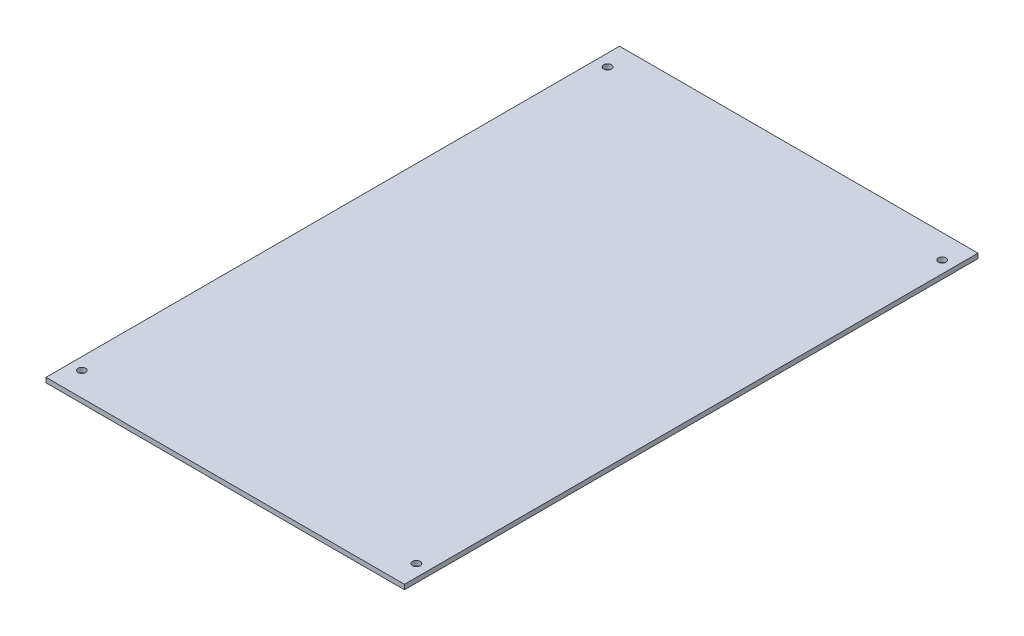
SolidWorks part; units mm, degrees
ref_plane "Front" through (0, 0, 0) normal (0, 0, 1) x (1, 0, 0)
ref_plane "Top" through (0, 0, 0) normal (0, 1, 0) x (1, 0, 0)
ref_plane "Right" through (0, 0, 0) normal (1, 0, 0) x (0, 0, -1)
sketch "Эскиз1" plane through (0, 0, 0) normal (0, 1, 0) x (1, 0, 0)
  line L1 (0, 0) -> (150, 0)
  line L2 (0, 0) -> (0, 240)
  line L3 (0, 240) -> (150, 240)
  line L4 (150, 0) -> (150, 240)
  dimension "D1" = 240
  dimension "D2" = 150
extrude "Бобышка-Вытянуть1" add sketch "Эскиз1" along normal blind 2
sketch "Эскиз2" plane through (0, 2, 0) normal (0, 1, 0) x (1, 0, 0)
  line L0 (0, 240) -> (0, 0) construction
  line L1 (150, 240) -> (0, 240) construction
  line L2 (75, 240) -> (75, 219.3641) construction
  line L3 (0, 120) -> (150, 120) construction
  line L4 (150, 0) -> (150, 240) construction
  circle A0 centre (5, 230) radius 1.6
  circle A1 centre (145, 230) radius 1.6
  circle A2 centre (145, 10) radius 1.6
  circle A3 centre (5, 10) radius 1.6
  dimension "D1" = 3.2
  dimension "D2" = 5
  dimension "D3" = 10
extrude "Вырез-Вытянуть1" cut sketch "Эскиз2" against normal through all
